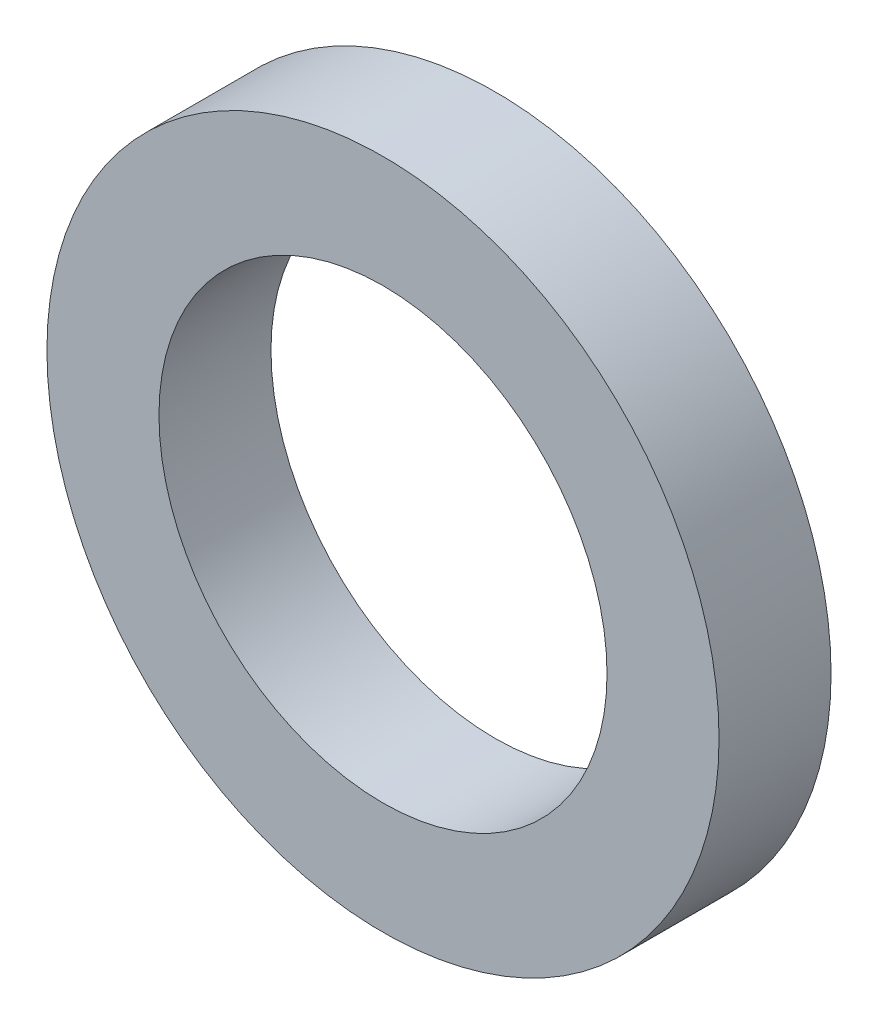
SolidWorks part; units mm, degrees
material "Rubber"
ref_plane "Front Plane" through (0, 0, 0) normal (0, 0, 1) x (1, 0, 0)
ref_plane "Top Plane" through (0, 0, 0) normal (0, 1, 0) x (1, 0, 0)
ref_plane "Right Plane" through (0, 0, 0) normal (1, 0, 0) x (0, 0, -1)
sketch "Sketch1" plane through (0, 0, 0) normal (0, 0, 1) x (1, 0, 0)
  circle A0 centre (0, 0) radius 14.2875
  circle A1 centre (0, 0) radius 9.525
  dimension "D1" = 19.05
  dimension "D2" = 28.575
extrude "Boss-Extrude1" add sketch "Sketch1" along normal blind 4.7625
